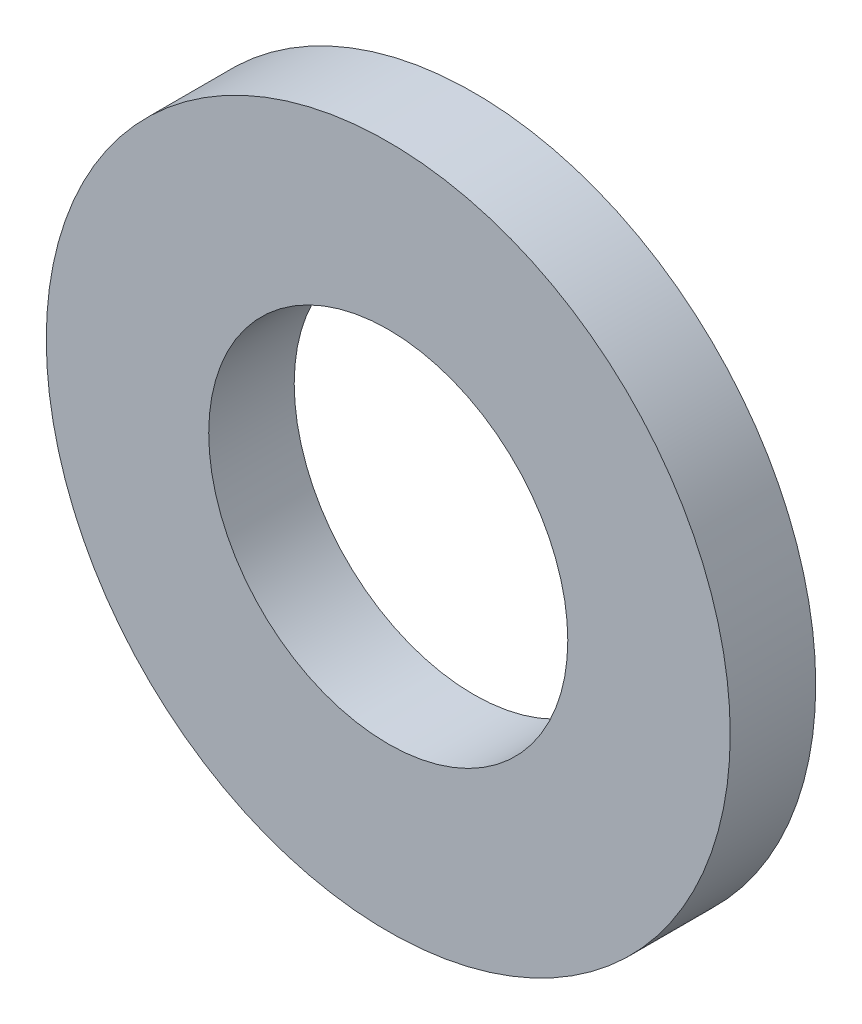
SolidWorks part; units mm, degrees
material "Nylon 6/10"
ref_plane "Face" through (0, 0, 0) normal (0, 0, 1) x (1, 0, 0)
ref_plane "Dessus" through (0, 0, 0) normal (0, 1, 0) x (1, 0, 0)
ref_plane "Droite" through (0, 0, 0) normal (1, 0, 0) x (0, 0, -1)
sketch "Esquisse1" plane through (0, 0, 0) normal (0, 0, 1) x (1, 0, 0)
  circle A0 centre (0, 0) radius 4
  circle A1 centre (0, 0) radius 2.1
  dimension "D1" = 8
  dimension "D2" = 4.2
extrude "Boss.-Extru.1" add sketch "Esquisse1" along normal blind 1
